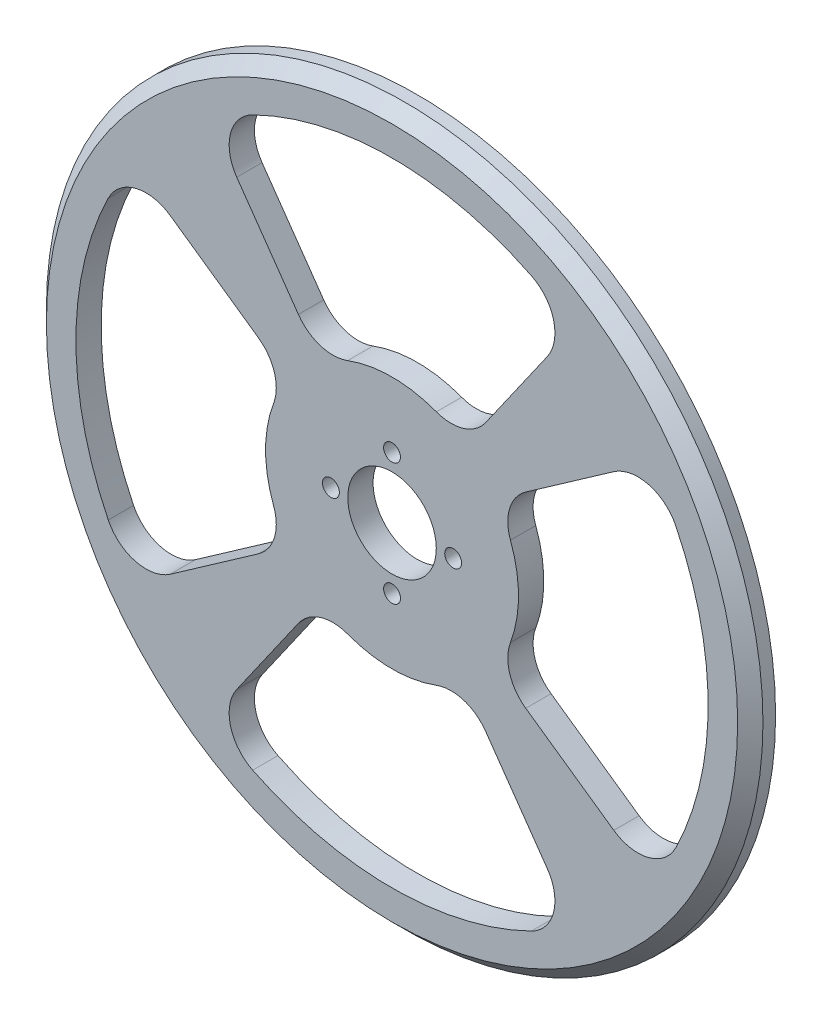
SolidWorks part; units mm, degrees
ref_plane "前视基准面" through (0, 0, 0) normal (0, 0, 1) x (1, 0, 0)
ref_plane "上视基准面" through (0, 0, 0) normal (0, 1, 0) x (1, 0, 0)
ref_plane "右视基准面" through (0, 0, 0) normal (1, 0, 0) x (0, 0, -1)
other "Configuration Table"
sketch "草图1" plane through (0, 0, 0) normal (0, 0, 1) x (1, 0, 0)
  line L2 (0, 75) -> (0, 0) construction
  line L3 (28.0994, 40.1301) -> (36.8386, 52.611)
  line L4 (-28.0994, 40.1301) -> (-36.8386, 52.611)
  line L5 (40.1301, 28.0994) -> (52.611, 36.8386)
  line L6 (40.1301, -28.0994) -> (52.611, -36.8386)
  line L7 (28.0994, -40.1301) -> (36.8386, -52.611)
  line L8 (-28.0994, -40.1301) -> (-36.8386, -52.611)
  line L9 (-40.1301, -28.0994) -> (-52.611, -36.8386)
  line L10 (-40.1301, 28.0994) -> (-52.611, 36.8386)
  line L12 (36.8386, 52.611) -> (22.2145, 31.7256)
  line L13 (-22.2145, 31.7256) -> (-36.8386, 52.611)
  line L15 (40.1301, 28.0994) -> (52.611, 36.8386)
  line L16 (40.1301, -28.0994) -> (52.611, -36.8386)
  line L17 (52.611, -36.8386) -> (31.7256, -22.2145)
  line L18 (28.0994, -40.1301) -> (36.8386, -52.611)
  line L19 (-28.0994, -40.1301) -> (-36.8386, -52.611)
  line L20 (-36.8386, -52.611) -> (-22.2145, -31.7256)
  line L21 (-40.1301, -28.0994) -> (-52.611, -36.8386)
  line L22 (-40.1301, 28.0994) -> (-52.611, 36.8386)
  line L23 (-52.611, 36.8386) -> (-31.7256, 22.2145)
  line L24 (28.0994, 40.1301) -> (22.2145, 31.7256)
  line L25 (52.611, 36.8386) -> (31.7256, 22.2145)
  line L26 (36.8386, 52.611) -> (28.0994, 40.1301)
  line L27 (28.0994, -40.1301) -> (22.2145, -31.7256)
  line L29 (-22.2145, -31.7256) -> (-28.0994, -40.1301)
  line L30 (-31.7256, -22.2145) -> (-40.1301, -28.0994)
  line L31 (-22.2145, 31.7256) -> (-28.0994, 40.1301)
  line L32 (31.7256, 22.2145) -> (40.1301, 28.0994)
  line L33 (31.7256, -22.2145) -> (40.1301, -28.0994)
  circle A0 centre (0, 0) radius 85
  arc A1 (33.0543, 67.3232) -> (-33.0543, 67.3232) centre (0, 0) ccw
  circle A3 centre (0, 0) radius 17.5
  arc A4 (36.8386, 52.611) -> (33.0543, 67.3232) centre (28.6471, 58.3468) ccw
  arc A7 (-33.0543, 67.3232) -> (-36.8386, 52.611) centre (-28.6471, 58.3468) ccw
  circle A8 centre (0, 0) radius 10.5
  arc A12 (67.3232, 33.0543) -> (52.611, 36.8386) centre (58.3468, 28.6471) ccw
  arc A13 (67.3232, -33.0543) -> (67.3232, 33.0543) centre (0, 0) ccw
  arc A14 (52.611, -36.8386) -> (67.3232, -33.0543) centre (58.3468, -28.6471) ccw
  arc A18 (33.0543, -67.3232) -> (36.8386, -52.611) centre (28.6471, -58.3468) ccw
  arc A19 (-33.0543, -67.3232) -> (33.0543, -67.3232) centre (0, 0) ccw
  arc A20 (-36.8386, -52.611) -> (-33.0543, -67.3232) centre (-28.6471, -58.3468) ccw
  arc A24 (-67.3232, -33.0543) -> (-52.611, -36.8386) centre (-58.3468, -28.6471) ccw
  arc A25 (-67.3232, 33.0543) -> (-67.3232, -33.0543) centre (0, 0) ccw
  arc A26 (-52.611, 36.8386) -> (-67.3232, 33.0543) centre (-58.3468, 28.6471) ccw
  arc A27 (10.5172, 28.096) -> (-10.5172, 28.096) centre (0, 0) ccw
  arc A28 (10.5172, 28.096) -> (22.2145, 31.7256) centre (14.023, 37.4614) ccw
  arc A29 (-10.5172, 28.096) -> (-22.2145, 31.7256) centre (-14.023, 37.4614) cw
  arc A30 (67.3232, 33.0543) -> (52.611, 36.8386) centre (58.3468, 28.6471) ccw
  arc A31 (67.3232, -33.0543) -> (67.3232, 33.0543) centre (0, 0) ccw
  arc A32 (52.611, -36.8386) -> (67.3232, -33.0543) centre (58.3468, -28.6471) ccw
  arc A33 (28.096, -10.5172) -> (31.7256, -22.2145) centre (37.4614, -14.023) ccw
  arc A34 (28.096, -10.5172) -> (28.096, 10.5172) centre (0, 0) ccw
  arc A35 (28.096, 10.5172) -> (31.7256, 22.2145) centre (37.4614, 14.023) cw
  arc A36 (33.0543, -67.3232) -> (36.8386, -52.611) centre (28.6471, -58.3468) ccw
  arc A37 (-33.0543, -67.3232) -> (33.0543, -67.3232) centre (0, 0) ccw
  arc A38 (-36.8386, -52.611) -> (-33.0543, -67.3232) centre (-28.6471, -58.3468) ccw
  arc A39 (-10.5172, -28.096) -> (-22.2145, -31.7256) centre (-14.023, -37.4614) ccw
  arc A40 (-10.5172, -28.096) -> (10.5172, -28.096) centre (0, 0) ccw
  arc A41 (10.5172, -28.096) -> (22.2145, -31.7256) centre (14.023, -37.4614) cw
  arc A42 (-67.3232, -33.0543) -> (-52.611, -36.8386) centre (-58.3468, -28.6471) ccw
  arc A43 (-67.3232, 33.0543) -> (-67.3232, -33.0543) centre (0, 0) ccw
  arc A44 (-52.611, 36.8386) -> (-67.3232, 33.0543) centre (-58.3468, 28.6471) ccw
  arc A45 (-28.096, 10.5172) -> (-31.7256, 22.2145) centre (-37.4614, 14.023) ccw
  arc A46 (-28.096, 10.5172) -> (-28.096, -10.5172) centre (0, 0) ccw
  arc A47 (-28.096, -10.5172) -> (-31.7256, -22.2145) centre (-37.4614, -14.023) cw
  point P21 (-43.0182, 61.4364)
  point P23 (-17.2073, 24.5746)
  point P60 (0, 0)
  point P106 (0, 0)
  dimension "D1" = 170
  dimension "D2" = 150
  dimension "D3" = 10
  dimension "D4" = 35
  dimension "D7" = 10
  dimension "D8" = 21
  dimension "D10" = 60
  dimension "D11" = 10
  dimension "D5" = 35
  dimension "D6" = 35
  dimension "D9" = 4
  dimension "D12" = 4
extrude "凸台-拉伸1" add sketch "草图1" along normal blind 6
sketch "草图2" plane through (0, 0, 6) normal (0, 0, 1) x (1, 0, 0)
  line L0 (0, 0) -> (0, 8.0053) construction
  circle A0 centre (0, 0) radius 14.5 construction
  circle A1 centre (0, 14.5) radius 2
  dimension "D1" = 29
  dimension "D2" = 4
extrude "切除-拉伸1" cut sketch "草图2" against normal blind 3
pattern_circular "阵列(圆周)2" count 4 over 360 about axis through (0, 0, 0) along (0, 0, 1) of "切除-拉伸1"
chamfer "倒角1" distance 3 angle 45 1 edges at (85, 0, 6)
